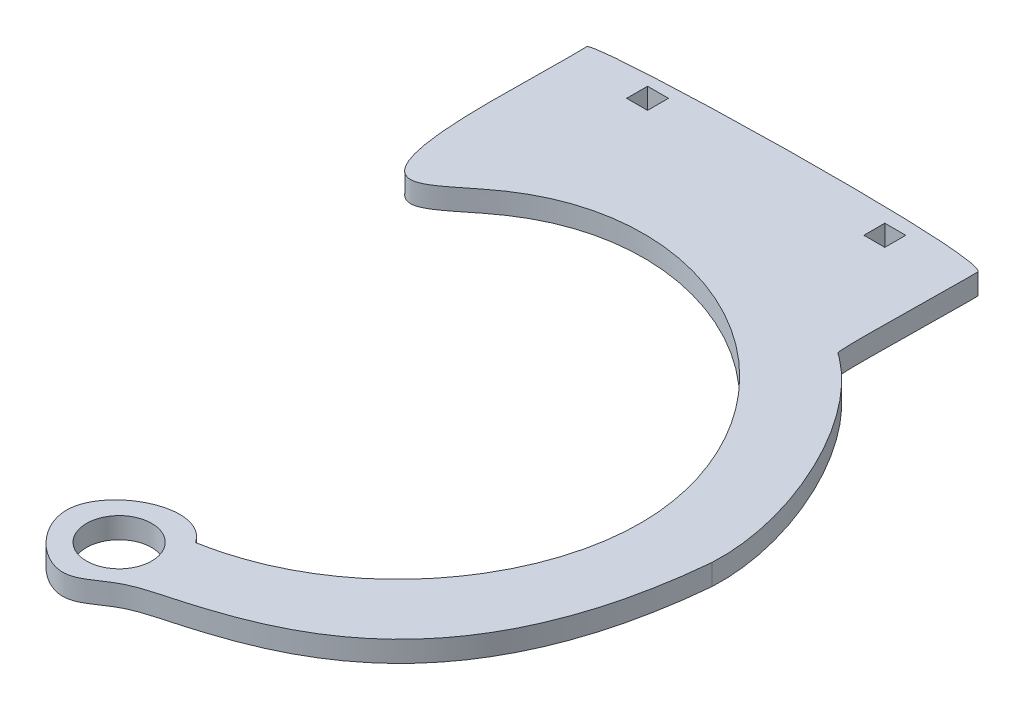
SolidWorks part; units mm, degrees
ref_plane "Front Plane" through (0, 0, 0) normal (0, 0, 1) x (1, 0, 0)
ref_plane "Top Plane" through (0, 0, 0) normal (0, 1, 0) x (1, 0, 0)
ref_plane "Right Plane" through (0, 0, 0) normal (1, 0, 0) x (0, 0, -1)
sketch "Sketch1" plane through (0, 0, 0) normal (0, 1, 0) x (1, 0, 0)
  line L1 (28, 35) -> (-28, 35) construction
  line L2 (28, 35) -> (28, 55) construction
  line L3 (28, 55) -> (-28, 55) construction
  line L4 (-28, 35) -> (-28, 55) construction
  line L5 (28, 35) -> (-28, 55) construction
  line L6 (28, 55) -> (-28, 35) construction
  circle A0 centre (0, 0) radius 40 construction
  circle A1 centre (0, -40) radius 4.75 construction
  circle A2 centre (0, -40) radius 7.75 construction
  circle A3 centre (0, 0) radius 35 construction
  circle A4 centre (0, 0) radius 45 construction
  spline S0 degree 3 poles (5.5216, -34.5617) (23.441, -31.4117) (44.4624, -2.8588) (20.375, 35.3512) (-9.4073, 38.5435) (-30.2262, 17.9966) (-27.7225, 45.3475) (-28.0432, 56.5042) (28.011, 57.688) (27.9669, 46.9503) (27.6537, 35.2407) (37.5515, 28.3605) (45.5872, 11.4498) (45, 0) knots 0 0 0 0 0.082838 0.148739 0.208271 0.224101 0.277627 0.277627 0.285968 0.285968 0.310948 0.310948 1 1 1 1
  spline S1 degree 3 poles (45, 0) (41.8351, -33.8354) (19.7672, -40.7526) (4.4778, -44.8709) (-0.8161, -50.4606) (-14.2628, -37.3252) (1.7546, -29.0679) (5.5216, -34.5617) knots 0 0 0 0 0.439042 0.498131 0.590884 0.751564 1 1 1 1
  point P8 (0, 45)
  point P19 (45.9688, 0)
  point P22 (0, 0)
  point P23 (0, 0)
  point P28 (6.2652, -44.5617)
  dimension "D1" = 80
  dimension "D2" = 9.5
  dimension "D3" = 15.5
  dimension "D4" = 70
  dimension "D5" = 90
  dimension "D6" = 20
  dimension "D7" = 56
extrude "Boss-Extrude1" add sketch "Sketch1" along normal blind 3
sketch "Sketch2" plane through (0, 3, 0) normal (0, 1, 0) x (1, 0, 0)
  circle A0 centre (0, 0) radius 40 construction
  circle A1 centre (0, -40) radius 4.675
  dimension "D1" = 80
  dimension "D2" = 9.35
extrude "Cut-Extrude1" cut sketch "Sketch2" against normal blind 3
extrude "Cut-Extrude2" cut sketch "Sketch3" against normal through all
sketch "Sketch3" plane through (-39.3167, 9, -84.9857) normal (0, 1, 0) x (1, 0, 0)
  line L1 (20.5911, -30.5235) -> (23.5911, -30.5235)
  line L2 (20.5911, -30.5235) -> (20.5911, -33.5235)
  line L3 (20.5911, -33.5235) -> (23.5911, -33.5235)
  line L4 (23.5911, -30.5235) -> (23.5911, -33.5235)
  line L7 (54.5911, -33.5235) -> (57.5911, -33.5235)
  line L8 (54.5911, -33.5235) -> (54.5911, -30.5235)
  line L9 (54.5911, -30.5235) -> (57.5911, -30.5235)
  line L10 (57.5911, -33.5235) -> (57.5911, -30.5235)
equation "\"D3@Sketch1\"=9.5+6"
